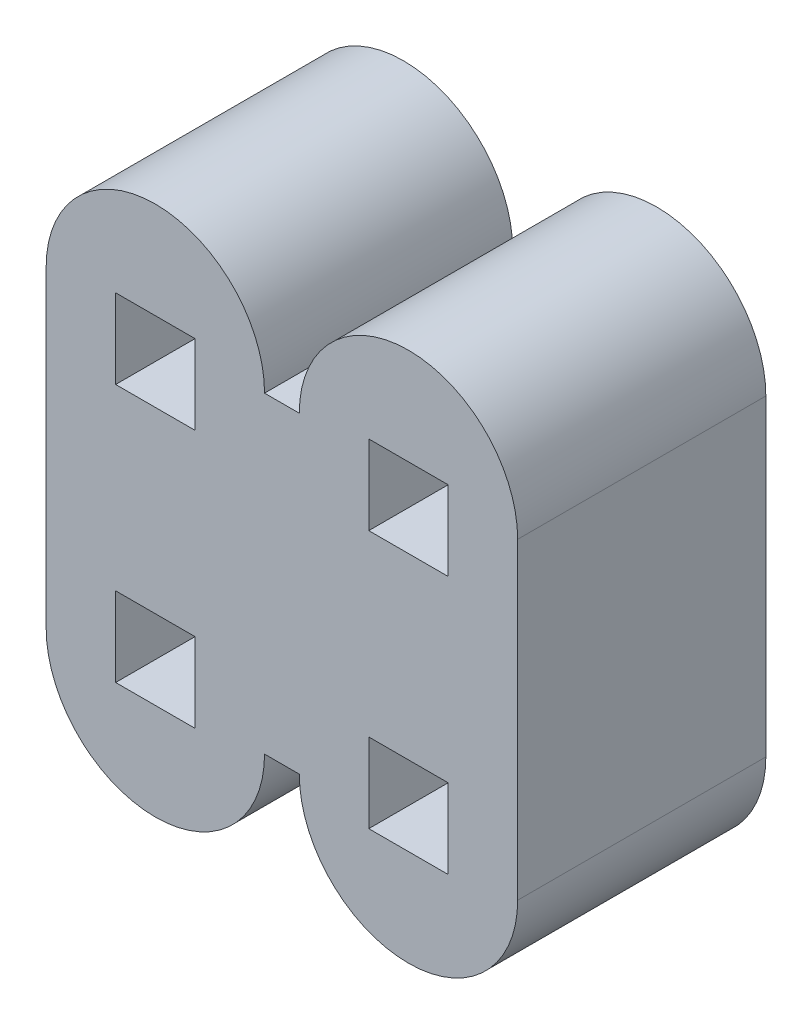
SolidWorks part; units mm, degrees
ref_plane "Přední rovina" through (0, 0, 0) normal (0, 0, 1) x (1, 0, 0)
ref_plane "Horní rovina" through (0, 0, 0) normal (0, 1, 0) x (1, 0, 0)
ref_plane "Pravá rovina" through (0, 0, 0) normal (1, 0, 0) x (0, 0, -1)
sketch "Skica1" plane through (0, 0, 0) normal (0, 0, 1) x (1, 0, 0)
  line L12 (-11.4466, -19.5901) -> (-11.4466, -16.4413) construction
  line L13 (-12.5466, -19.5901) -> (-12.5466, -16.4413)
  line L14 (-10.3466, -19.5901) -> (-10.3466, -16.4413)
  line L18 (-13.9966, -19.5901) -> (-13.9966, -16.4413) construction
  line L19 (-15.0966, -19.5901) -> (-15.0966, -16.4413)
  line L20 (-12.8966, -19.5901) -> (-12.8966, -16.4413)
  line L34 (-10.3466, -19.5901) -> (-10.3466, -16.4413)
  line L37 (-12.8966, -19.5901) -> (-12.5466, -19.5901)
  line L38 (-12.8966, -19.5901) -> (-12.8966, -16.4413)
  line L39 (-12.8966, -16.4413) -> (-12.5466, -16.4413)
  line L40 (-12.5466, -19.5901) -> (-12.5466, -16.4413)
  arc A8 (-12.5466, -19.5901) -> (-10.3466, -19.5901) centre (-11.4466, -19.5901) ccw
  arc A9 (-10.3466, -16.4413) -> (-12.5466, -16.4413) centre (-11.4466, -16.4413) ccw
  arc A12 (-15.0966, -19.5901) -> (-12.8966, -19.5901) centre (-13.9966, -19.5901) ccw
  arc A13 (-12.8966, -16.4413) -> (-15.0966, -16.4413) centre (-13.9966, -16.4413) ccw
  point P30 (-11.4466, -18.0157)
  point P44 (-13.9966, -18.0157)
  dimension "D2" = 2.2
  dimension "D3" = 0.35
  dimension "D8" = 2.2
extrude "Přidat vysunutím1" add sketch "Skica1" along normal blind 2.5 contours L20 A13 L19 A12 | L39 L20 L37 L13 | L14 A9 L13 A8
sketch "Skica2" plane through (0, 0, 2.5) normal (0, 0, 1) x (1, 0, 0)
  line L0 (-15.0966, -18.0157) -> (-10.3466, -18.0157) construction
  line L1 (-14.3966, -16.3157) -> (-13.5966, -16.3157)
  line L2 (-14.3966, -16.3157) -> (-14.3966, -17.1157)
  line L3 (-14.3966, -17.1157) -> (-13.5966, -17.1157)
  line L4 (-13.5966, -16.3157) -> (-13.5966, -17.1157)
  line L5 (-14.3966, -18.9157) -> (-13.5966, -18.9157)
  line L6 (-14.3966, -18.9157) -> (-14.3966, -19.7157)
  line L7 (-14.3966, -19.7157) -> (-13.5966, -19.7157)
  line L8 (-13.5966, -18.9157) -> (-13.5966, -19.7157)
  line L9 (-15.0966, -19.5901) -> (-15.0966, -16.4413) construction
  line L10 (-10.3466, -19.5901) -> (-10.3466, -16.4413) construction
  line L11 (-12.7216, -16.4413) -> (-12.7216, -19.5901) construction
  line L12 (-11.8466, -16.3157) -> (-11.0466, -16.3157)
  line L13 (-11.8466, -16.3157) -> (-11.8466, -17.1157)
  line L14 (-11.8466, -17.1157) -> (-11.0466, -17.1157)
  line L15 (-11.0466, -16.3157) -> (-11.0466, -17.1157)
  line L16 (-11.8466, -18.9157) -> (-11.0466, -18.9157)
  line L17 (-11.8466, -18.9157) -> (-11.8466, -19.7157)
  line L18 (-11.8466, -19.7157) -> (-11.0466, -19.7157)
  line L19 (-11.0466, -18.9157) -> (-11.0466, -19.7157)
  line L20 (-12.8966, -16.4413) -> (-12.5466, -16.4413) construction
  line L21 (-12.8966, -19.5901) -> (-12.5466, -19.5901) construction
  line L22 (-13.9966, -17.1157) -> (-13.9966, -18.9157) construction
  line L23 (-11.4466, -17.1157) -> (-11.4466, -18.9157) construction
  line L24 (-13.9966, -18.0157) -> (-11.4466, -18.0157) construction
  dimension "D2" = 0.8
  dimension "D3" = 0.7
  dimension "D4" = 1.8
  dimension "D5" = 0.7
  dimension "D10" = 1.8
  dimension "D25" = 0.8
  dimension "D26" = 0.8
extrude "Odebrat vysunutím1" cut sketch "Skica2" against normal blind 2.5
